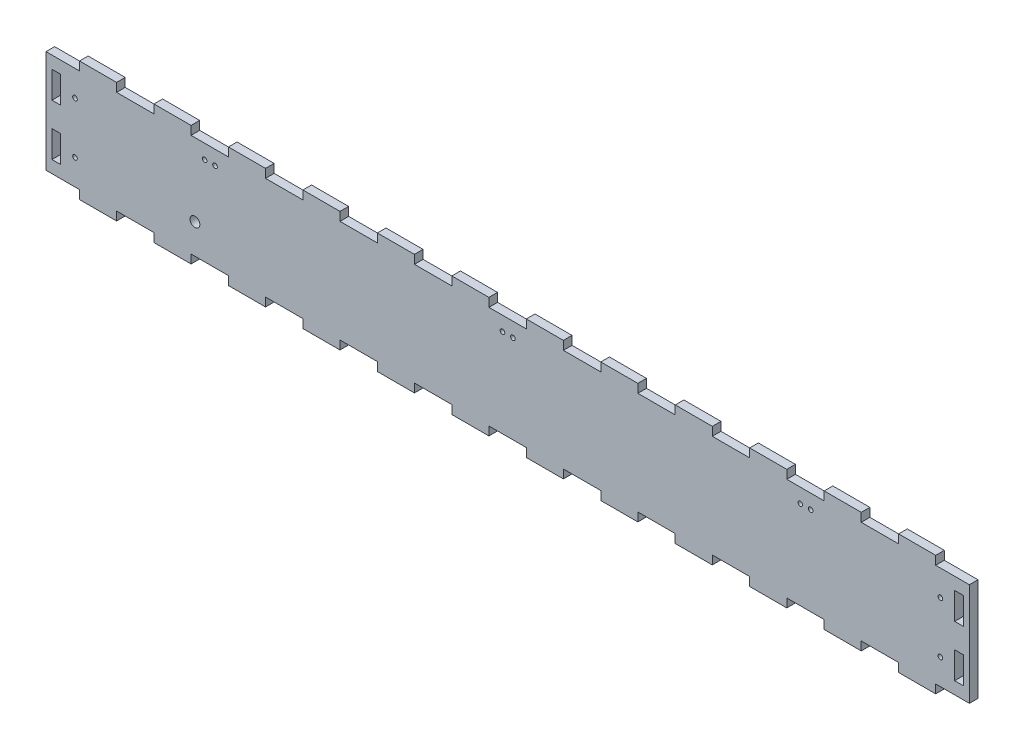
SolidWorks part; units mm, degrees
ref_plane "Спереди" through (0, 0, 0) normal (0, 0, 1) x (1, 0, 0)
ref_plane "Сверху" through (0, 0, 0) normal (0, 1, 0) x (1, 0, 0)
ref_plane "Справа" through (0, 0, 0) normal (1, 0, 0) x (0, 0, -1)
other "Configuration Table"
sketch "Sketch1" plane through (0, 0, 0) normal (0, 0, 1) x (1, 0, 0)
  line L0 (-237.5, 34.5) -> (-237.5, 40.3)
  line L1 (310, -34.5) -> (287.4, -34.5)
  line L2 (310, -34.5) -> (310, 34.5)
  line L3 (310, 34.5) -> (287.4, 34.5)
  line L4 (-310, -34.5) -> (-310, 34.5)
  line L5 (310, -34.5) -> (-310, 34.5) construction
  line L6 (310, 34.5) -> (-310, -34.5) construction
  line L8 (-287.5, 34.5) -> (-287.5, 40.3)
  line L9 (-287.5, 40.3) -> (-262.6, 40.3)
  line L10 (-262.6, 34.5) -> (-262.6, 40.3)
  line L12 (-212.6, 34.5) -> (-212.6, 40.3)
  line L13 (-237.5, 40.3) -> (-212.6, 40.3)
  line L14 (-187.5, 34.5) -> (-187.5, 40.3)
  line L16 (-162.6, 34.5) -> (-162.6, 40.3)
  line L17 (-187.5, 40.3) -> (-162.6, 40.3)
  line L18 (-137.5, 34.5) -> (-137.5, 40.3)
  line L20 (-112.6, 34.5) -> (-112.6, 40.3)
  line L21 (-137.5, 40.3) -> (-112.6, 40.3)
  line L22 (-87.5, 34.5) -> (-87.5, 40.3)
  line L24 (-62.6, 34.5) -> (-62.6, 40.3)
  line L25 (-87.5, 40.3) -> (-62.6, 40.3)
  line L26 (-37.5, 34.5) -> (-37.5, 40.3)
  line L28 (-12.6, 34.5) -> (-12.6, 40.3)
  line L29 (-37.5, 40.3) -> (-12.6, 40.3)
  line L30 (12.5, 34.5) -> (12.5, 40.3)
  line L32 (37.4, 34.5) -> (37.4, 40.3)
  line L33 (12.5, 40.3) -> (37.4, 40.3)
  line L34 (62.5, 34.5) -> (62.5, 40.3)
  line L36 (87.4, 34.5) -> (87.4, 40.3)
  line L37 (62.5, 40.3) -> (87.4, 40.3)
  line L38 (112.5, 34.5) -> (112.5, 40.3)
  line L40 (137.4, 34.5) -> (137.4, 40.3)
  line L41 (112.5, 40.3) -> (137.4, 40.3)
  line L42 (162.5, 34.5) -> (162.5, 40.3)
  line L44 (187.4, 34.5) -> (187.4, 40.3)
  line L45 (162.5, 40.3) -> (187.4, 40.3)
  line L46 (212.5, 34.5) -> (212.5, 40.3)
  line L48 (237.4, 34.5) -> (237.4, 40.3)
  line L49 (212.5, 40.3) -> (237.4, 40.3)
  line L50 (262.5, 34.5) -> (262.5, 40.3)
  line L52 (287.4, 34.5) -> (287.4, 40.3)
  line L53 (262.5, 40.3) -> (287.4, 40.3)
  line L54 (0, 0) -> (310, 0) construction
  line L55 (-237.5, -34.5) -> (-237.5, -40.3)
  line L57 (-287.5, -34.5) -> (-287.5, -40.3)
  line L58 (-287.5, -40.3) -> (-262.6, -40.3)
  line L59 (-262.6, -34.5) -> (-262.6, -40.3)
  line L61 (-212.6, -34.5) -> (-212.6, -40.3)
  line L62 (-237.5, -40.3) -> (-212.6, -40.3)
  line L63 (-187.5, -34.5) -> (-187.5, -40.3)
  line L65 (-162.6, -34.5) -> (-162.6, -40.3)
  line L66 (-187.5, -40.3) -> (-162.6, -40.3)
  line L67 (-137.5, -34.5) -> (-137.5, -40.3)
  line L69 (-112.6, -34.5) -> (-112.6, -40.3)
  line L70 (-137.5, -40.3) -> (-112.6, -40.3)
  line L71 (-87.5, -34.5) -> (-87.5, -40.3)
  line L73 (-62.6, -34.5) -> (-62.6, -40.3)
  line L74 (-87.5, -40.3) -> (-62.6, -40.3)
  line L75 (-37.5, -34.5) -> (-37.5, -40.3)
  line L77 (-12.6, -34.5) -> (-12.6, -40.3)
  line L78 (-37.5, -40.3) -> (-12.6, -40.3)
  line L79 (12.5, -34.5) -> (12.5, -40.3)
  line L81 (37.4, -34.5) -> (37.4, -40.3)
  line L82 (12.5, -40.3) -> (37.4, -40.3)
  line L83 (62.5, -34.5) -> (62.5, -40.3)
  line L85 (87.4, -34.5) -> (87.4, -40.3)
  line L86 (62.5, -40.3) -> (87.4, -40.3)
  line L87 (112.5, -34.5) -> (112.5, -40.3)
  line L89 (137.4, -34.5) -> (137.4, -40.3)
  line L90 (112.5, -40.3) -> (137.4, -40.3)
  line L91 (162.5, -34.5) -> (162.5, -40.3)
  line L93 (187.4, -34.5) -> (187.4, -40.3)
  line L94 (162.5, -40.3) -> (187.4, -40.3)
  line L95 (212.5, -34.5) -> (212.5, -40.3)
  line L97 (237.4, -34.5) -> (237.4, -40.3)
  line L98 (212.5, -40.3) -> (237.4, -40.3)
  line L99 (262.5, -34.5) -> (262.5, -40.3)
  line L101 (287.4, -34.5) -> (287.4, -40.3)
  line L102 (262.5, -40.3) -> (287.4, -40.3)
  line L103 (303.075, 26.25) -> (303.075, 34.5) construction
  line L104 (306, 26.25) -> (300.15, 26.25)
  line L105 (306, 26.25) -> (306, 8.25)
  line L106 (306, 8.25) -> (300.15, 8.25)
  line L107 (300.15, 26.25) -> (300.15, 8.25)
  line L108 (303.075, 8.25) -> (303.075, 0) construction
  line L109 (306, -8.25) -> (300.15, -8.25)
  line L110 (300.15, -26.25) -> (300.15, -8.25)
  line L111 (306, -26.25) -> (300.15, -26.25)
  line L112 (306, -26.25) -> (306, -8.25)
  line L113 (0, 0) -> (0, 34.5) construction
  line L114 (-306, -26.25) -> (-306, -8.25)
  line L115 (-306, -26.25) -> (-300.15, -26.25)
  line L116 (-300.15, -26.25) -> (-300.15, -8.25)
  line L117 (-306, -8.25) -> (-300.15, -8.25)
  line L118 (-306, 8.25) -> (-300.15, 8.25)
  line L119 (-300.15, 26.25) -> (-300.15, 8.25)
  line L120 (-306, 26.25) -> (-300.15, 26.25)
  line L121 (-306, 26.25) -> (-306, 8.25)
  line L122 (-287.5, 34.5) -> (-310, 34.5)
  line L127 (-237.5, 34.5) -> (-262.6, 34.5)
  line L128 (-187.5, 34.5) -> (-212.6, 34.5)
  line L129 (-137.5, 34.5) -> (-162.6, 34.5)
  line L130 (-87.5, 34.5) -> (-112.6, 34.5)
  line L131 (-37.5, 34.5) -> (-62.6, 34.5)
  line L132 (12.5, 34.5) -> (-12.6, 34.5)
  line L133 (62.5, 34.5) -> (37.4, 34.5)
  line L134 (112.5, 34.5) -> (87.4, 34.5)
  line L135 (162.5, 34.5) -> (137.4, 34.5)
  line L136 (212.5, 34.5) -> (187.4, 34.5)
  line L137 (262.5, 34.5) -> (237.4, 34.5)
  line L138 (262.5, -34.5) -> (237.4, -34.5)
  line L139 (-300.15, 17.25) -> (-290.53, 17.25) construction
  line L141 (212.5, -34.5) -> (187.4, -34.5)
  line L143 (162.5, -34.5) -> (137.4, -34.5)
  line L145 (112.5, -34.5) -> (87.4, -34.5)
  line L147 (62.5, -34.5) -> (37.4, -34.5)
  line L149 (12.5, -34.5) -> (-12.6, -34.5)
  line L151 (-37.5, -34.5) -> (-62.6, -34.5)
  line L153 (-87.5, -34.5) -> (-112.6, -34.5)
  line L155 (-137.5, -34.5) -> (-162.6, -34.5)
  line L157 (-187.5, -34.5) -> (-212.6, -34.5)
  line L159 (-237.5, -34.5) -> (-262.6, -34.5)
  line L160 (-287.5, -34.5) -> (-310, -34.5)
  circle A0 centre (-210, -14.5) radius 3.3
  circle A1 centre (-290.53, 17.25) radius 1.55
  circle A2 centre (-290.53, -17.25) radius 1.55
  circle A3 centre (290.53, -17.25) radius 1.55
  circle A4 centre (290.53, 17.25) radius 1.55
  circle A5 centre (3.5, 24.88) radius 1.55
  circle A6 centre (-3.5, 24.88) radius 1.55
  circle A7 centre (196.5, 24.88) radius 1.55
  circle A8 centre (203.5, 24.88) radius 1.55
  circle A9 centre (-196.5, 24.88) radius 1.55
  circle A10 centre (-203.5, 24.88) radius 1.55
  point P0 (0, 0)
  dimension "D10" = 6.6
  dimension "D16" = 3.1
  dimension "D19" = 3.1
  dimension "D1" = 620
  dimension "D2" = 22.5
  dimension "D3" = 24.9
  dimension "D4" = 5.8
  dimension "D6" = 5.8
  dimension "D8" = 100
  dimension "D9" = 20
  dimension "D11" = 69
  dimension "D12" = 4
  dimension "D13" = 18
  dimension "D14" = 5.85
  dimension "D15" = 9.62
  dimension "D17" = 9.62
  dimension "D18" = 3.5
  dimension "D5" = 12
  dimension "D7" = 12
  dimension "D20" = 2
  dimension "D21" = 2
extrude "Boss-Extrude1" add sketch "Sketch1" along normal blind 5.8
